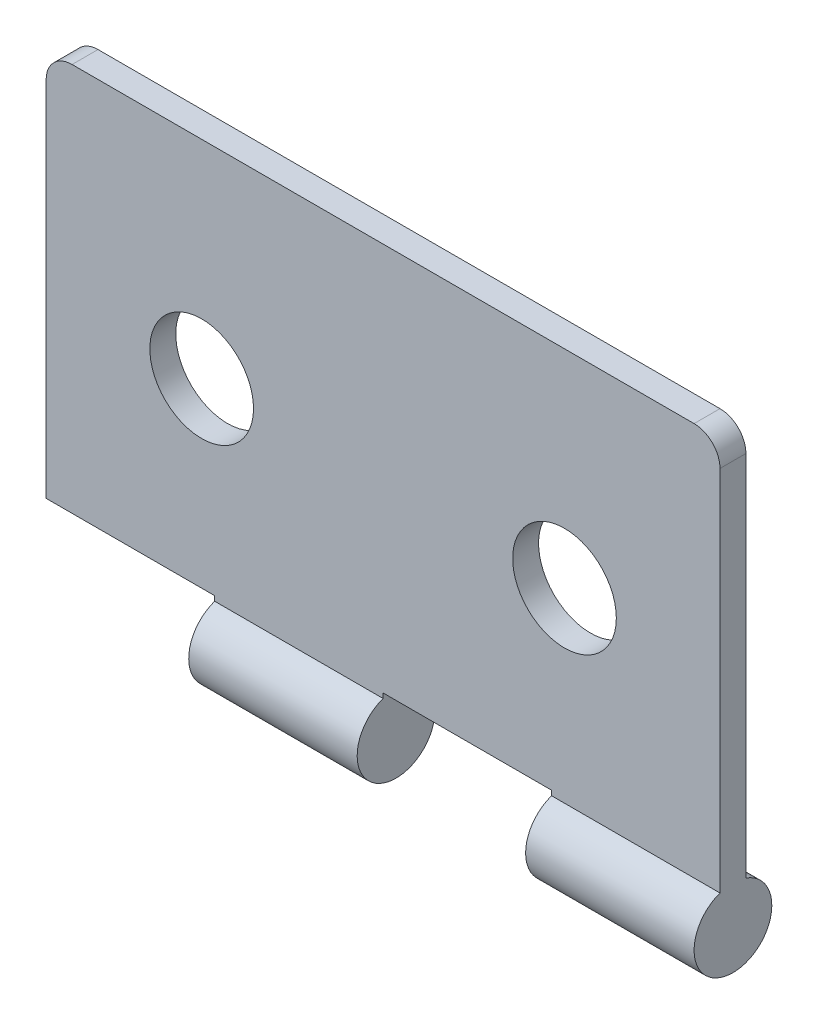
SolidWorks part; units mm, degrees
ref_plane "Front Plane" through (0, 0, 0) normal (0, 0, 1) x (1, 0, 0)
ref_plane "Top Plane" through (0, 0, 0) normal (0, 1, 0) x (1, 0, 0)
ref_plane "Right Plane" through (0, 0, 0) normal (1, 0, 0) x (0, 0, -1)
sketch "Sketch1" plane through (0, 0, 0) normal (0, 0, 1) x (1, 0, 0)
  line L1 (0, 0) -> (26, 0)
  line L2 (0, 0) -> (0, 15)
  line L3 (0, 15) -> (26, 15)
  line L4 (26, 0) -> (26, 15)
  circle A0 centre (6, 7) radius 2
  circle A1 centre (20, 7) radius 2
  dimension "D3" = 4
  dimension "D4" = 4
  dimension "D1" = 26
  dimension "D2" = 15
  dimension "D5" = 8
  dimension "D6" = 8
  dimension "D7" = 6
  dimension "D8" = 6
extrude "Boss-Extrude1" add sketch "Sketch1" along normal blind 1
fillet "Fillet1" radius 1 2 edges at (26, 15, 0.5) (0, 15, 0.5)
sketch "Sketch3" plane through (0, 0, 0) normal (1, 0, 0) x (0, 0, -1)
  line L0 (-0.5, 0) -> (-0.5, -1.6) construction
  line L1 (-1, 0) -> (0, 0) construction
  circle A0 centre (-0.5, -1.6) radius 1.5
  point P5 (0, 0)
  dimension "D1" = 3
  dimension "D2" = 1.6
extrude "Boss-Extrude2" add sketch "Sketch3" along normal up to surface (26 mm away) separate body up to face at (26, 7, 0.5)
sketch "Sketch6" plane through (0, 0, 0) normal (0, -1, 0) x (1, 0, 0)
  line L4 (0, 0) -> (26, 0)
  line L5 (26, 0) -> (26, 1)
  line L6 (26, 1) -> (0, 1)
  line L7 (0, 1) -> (0, 0)
  line L8 (0, 0) -> (26, 0)
  line L9 (26, 0) -> (26, 1)
  line L10 (26, 1) -> (0, 1)
  line L11 (0, 1) -> (0, 0)
  dimension "D1" = 0
extrude "Boss-Extrude3" add sketch "Sketch6" along normal up to surface (0.1858 mm away)
sketch "Sketch8" plane through (0, 0, 0) normal (0, 0, 1) x (1, 0, 0)
  line L0 (0, 0) -> (26, 0) construction
  line L1 (26, -0.1858) -> (26, 14) construction
  line L2 (0, -3.1) -> (26, -3.1) construction
  line L3 (0, 0) -> (6.5, 0)
  line L4 (0, 0) -> (0, -3.1)
  line L5 (0, -3.1) -> (6.5, -3.1)
  line L6 (6.5, 0) -> (6.5, -3.1)
  line L8 (13, 0) -> (19.5, 0)
  line L9 (13, 0) -> (13, -3.1)
  line L10 (13, -3.1) -> (19.5, -3.1)
  line L11 (19.5, 0) -> (19.5, -3.1)
  dimension "D1" = 6.5
  dimension "D2" = 6.5
  dimension "D3" = 6.5
extrude "Cut-Extrude1" cut sketch "Sketch8" against normal through all both and the other way through all
